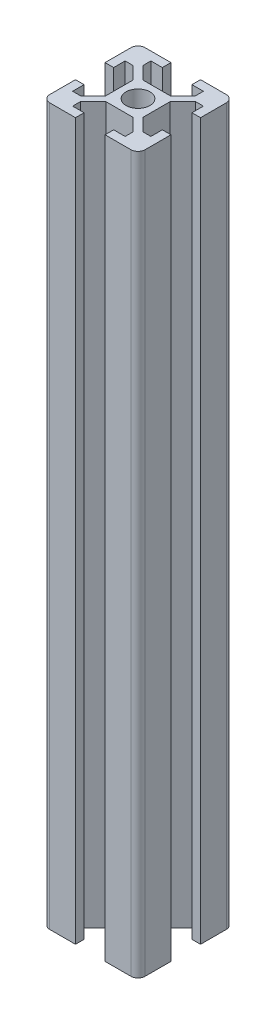
SolidWorks part; units mm, degrees
ref_plane "前视基准面" through (0, 0, 0) normal (0, 0, 1) x (1, 0, 0)
ref_plane "上视基准面" through (0, 0, 0) normal (0, 1, 0) x (1, 0, 0)
ref_plane "右视基准面" through (0, 0, 0) normal (1, 0, 0) x (0, 0, -1)
sketch "草图2" plane through (0, 0, 0) normal (0, 1, 0) x (1, 0, 0)
  line L0 (-2.8393, -3.9) -> (-5.5, -6.5607)
  line L1 (-8.5, 10) -> (-3.1, 10)
  line L2 (-2.8393, 3.9) -> (2.8393, 3.9)
  line L3 (-3.9, 2.8393) -> (-3.9, -2.8393)
  line L4 (-2.8393, -3.9) -> (2.8393, -3.9)
  line L5 (3.9, 2.8393) -> (3.9, -2.8393)
  line L6 (-3.9, -2.8393) -> (-6.5607, -5.5)
  line L7 (-10, 8.5) -> (-10, 3.1)
  line L8 (-10, 3.1) -> (-8.2, 3.1)
  line L9 (-8.2, 3.1) -> (-8.2, 5.5)
  line L10 (-8.2, 5.5) -> (-6.5607, 5.5)
  line L11 (-10, -8.5) -> (-10, -3.1)
  line L12 (-8.5, -10) -> (-3.1, -10)
  line L13 (-3.9, 2.8393) -> (-6.5607, 5.5)
  line L14 (10, -3.1) -> (8.2, -3.1)
  line L15 (-3.1, -10) -> (-3.1, -8.2)
  line L16 (3.1, -8.2) -> (5.5, -8.2)
  line L17 (8.2, -3.1) -> (8.2, -5.5)
  line L18 (5.5, -8.2) -> (5.5, -6.5607)
  line L19 (-2.8393, 3.9) -> (-5.5, 6.5607)
  line L20 (-5.5, 8.2) -> (-5.5, 6.5607)
  line L21 (-10, -3.1) -> (-8.2, -3.1)
  line L22 (-3.1, 8.2) -> (-5.5, 8.2)
  line L23 (8.2, -5.5) -> (6.5607, -5.5)
  line L24 (3.1, -10) -> (3.1, -8.2)
  line L25 (-8.2, -5.5) -> (-6.5607, -5.5)
  line L26 (-5.5, -8.2) -> (-5.5, -6.5607)
  line L27 (8.5, -10) -> (3.1, -10)
  line L28 (10, -8.5) -> (10, -3.1)
  line L29 (3.9, -2.8393) -> (6.5607, -5.5)
  line L30 (-8.2, -3.1) -> (-8.2, -5.5)
  line L31 (-3.1, -8.2) -> (-5.5, -8.2)
  line L32 (2.8393, -3.9) -> (5.5, -6.5607)
  line L33 (-3.1, 10) -> (-3.1, 8.2)
  line L34 (3.1, 10) -> (3.1, 8.2)
  line L35 (10, 3.1) -> (8.2, 3.1)
  line L36 (2.8393, 3.9) -> (5.5, 6.5607)
  line L37 (3.9, 2.8393) -> (6.5607, 5.5)
  line L38 (10, 8.5) -> (10, 3.1)
  line L39 (8.5, 10) -> (3.1, 10)
  line L40 (8.2, 5.5) -> (6.5607, 5.5)
  line L41 (5.5, 8.2) -> (5.5, 6.5607)
  line L42 (8.2, 3.1) -> (8.2, 5.5)
  line L43 (3.1, 8.2) -> (5.5, 8.2)
  circle A0 centre (0, 0) radius 2.5
  arc A1 (-8.5, 10) -> (-10, 8.5) centre (-8.5, 8.5) ccw
  arc A2 (8.5, 10) -> (10, 8.5) centre (8.5, 8.5) cw
  arc A3 (8.5, -10) -> (10, -8.5) centre (8.5, -8.5) ccw
  arc A4 (-8.5, -10) -> (-10, -8.5) centre (-8.5, -8.5) cw
  point P0 (0, 0)
  point P22 (0, 0)
  point P25 (0, 0)
  dimension "D1" = 5
  dimension "D5" = 1.5
  dimension "D2" = 20
  dimension "D3" = 20
  dimension "D4" = 6.2
  dimension "D6" = 5.6787
extrude "凸台-拉伸1" add sketch "草图2" along normal blind 150
